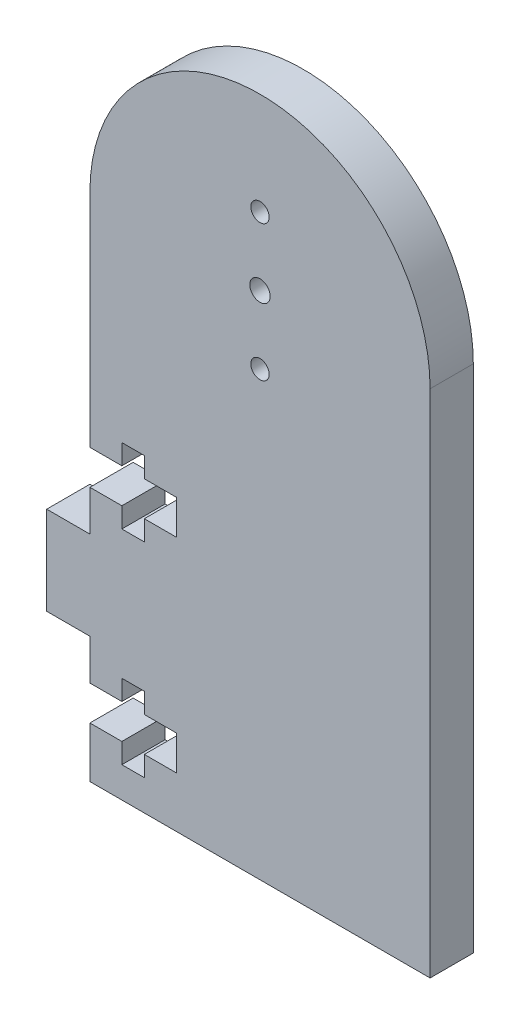
SolidWorks part; units mm, degrees
ref_plane "Front Plane" through (0, 0, 0) normal (0, 0, 1) x (1, 0, 0)
ref_plane "Top Plane" through (0, 0, 0) normal (0, 1, 0) x (1, 0, 0)
ref_plane "Right Plane" through (0, 0, 0) normal (1, 0, 0) x (0, 0, -1)
sketch "Sketch1" plane through (0, 0, 0) normal (0, 0, 1) x (1, 0, 0)
  line L0 (-25, 0) -> (25, 0) construction
  line L2 (-25, 0) -> (-25, -75)
  line L3 (-25, -75) -> (25, -75)
  line L4 (25, 0) -> (25, -75)
  arc A0 (25, 0) -> (-25, 0) centre (0, 0) ccw
  dimension "D1" = 50
  dimension "D2" = 75
  dimension "D3" = 50
extrude "Boss-Extrude1" add sketch "Sketch1" along normal blind 6.35
sketch "Sketch2" plane through (0, 0, 6.35) normal (0, 0, 1) x (1, 0, 0)
  line L0 (0, 10) -> (0, -10) construction
  line L1 (0, 25) -> (0, -75) construction
  line L2 (-25, -75) -> (25, -75) construction
  circle A0 centre (0, 0) radius 1.5
  circle A1 centre (0, 10) radius 1.35
  circle A2 centre (0, -10) radius 1.35
  arc A3 (25, 0) -> (-25, 0) centre (0, 0) ccw construction
  dimension "D1" = 3
  dimension "D3" = 2.7
  dimension "D2" = 20
extrude "Cut-Extrude1" cut sketch "Sketch2" against normal through all
sketch "Sketch6" plane through (0, 0, 6.35) normal (0, 0, 1) x (1, 0, 0)
  line L0 (-25, -65) -> (-12.3, -65) construction
  line L1 (-12.3, -67.54) -> (-16.999, -67.54)
  line L2 (-25, -67.54) -> (-25, -62.46)
  line L3 (-12.3, -62.46) -> (-16.999, -62.46)
  line L4 (-20.301, -67.54) -> (-25, -67.54)
  line L5 (-20.301, -70.4991) -> (-20.301, -67.54)
  line L6 (-20.301, -70.4991) -> (-16.999, -70.4991)
  line L7 (-16.999, -70.4991) -> (-16.999, -67.54)
  line L8 (-20.301, -59.5009) -> (-16.999, -59.5009)
  line L9 (-20.301, -62.46) -> (-20.301, -59.5009)
  line L10 (-20.301, -62.46) -> (-25, -62.46)
  line L11 (-16.999, -62.46) -> (-16.999, -59.5009)
  line L12 (-12.3, -62.46) -> (-12.3, -67.54)
  line L13 (-25, -65) -> (-12.3, -65) construction
  line L15 (-25, 0) -> (-25, -75) construction
  line L16 (-25, -75) -> (25, -75) construction
  line L17 (-12.3, -37.54) -> (-16.999, -37.54)
  line L18 (-25, -37.54) -> (-25, -32.46)
  line L19 (-12.3, -32.46) -> (-16.999, -32.46)
  line L20 (-20.301, -37.54) -> (-25, -37.54)
  line L21 (-20.301, -40.4991) -> (-20.301, -37.54)
  line L22 (-20.301, -40.4991) -> (-16.999, -40.4991)
  line L23 (-16.999, -40.4991) -> (-16.999, -37.54)
  line L24 (-20.301, -29.5009) -> (-16.999, -29.5009)
  line L25 (-20.301, -32.46) -> (-20.301, -29.5009)
  line L26 (-20.301, -32.46) -> (-25, -32.46)
  line L27 (-16.999, -32.46) -> (-16.999, -29.5009)
  line L28 (-12.3, -32.46) -> (-12.3, -37.54)
  line L29 (-25, -35) -> (-12.3, -35) construction
  line L30 (-25, -35) -> (-12.3, -35) construction
  point P4 (-25, -65)
  point P25 (-25, -35)
  dimension "D1" = 5.08
  dimension "D2" = 3.302
  dimension "D3" = 10.9982
  dimension "D4" = 12.7
  dimension "D5" = 10
  dimension "D7" = 30
  dimension "D6" = 2
extrude "Cut-Extrude3" cut sketch "Sketch6" against normal through all
sketch "Sketch7" plane through (0, 0, 6.35) normal (0, 0, 1) x (1, 0, 0)
  line L0 (-25, -37.54) -> (-25, -62.46) construction
  line L1 (-31.35, -43.5) -> (-25, -43.5)
  line L2 (-31.35, -43.5) -> (-31.35, -56.5)
  line L3 (-31.35, -56.5) -> (-25, -56.5)
  line L4 (-25, -43.5) -> (-25, -56.5)
  point P6 (-25, -50)
  dimension "D1" = 6.35
  dimension "D2" = 13
extrude "Boss-Extrude3" add sketch "Sketch7" against normal blind 6.35
